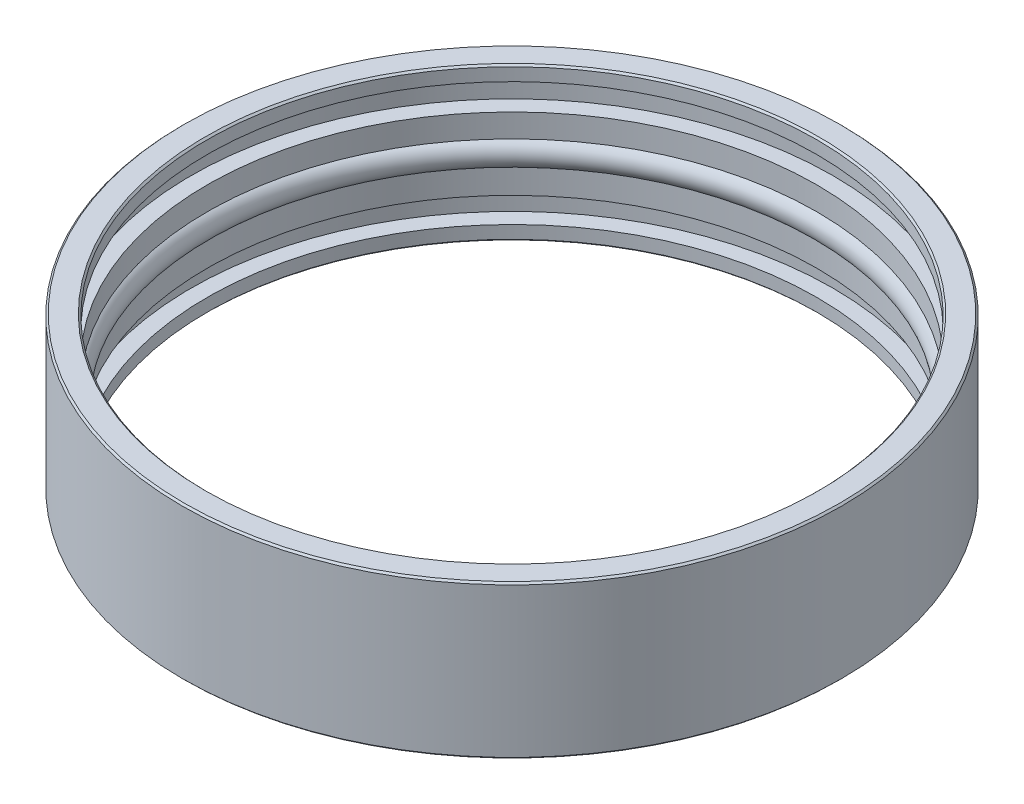
SolidWorks part; units mm, degrees
ref_plane "Plano frontal" through (0, 0, 0) normal (0, 0, 1) x (1, 0, 0)
ref_plane "Plano superior" through (0, 0, 0) normal (0, 1, 0) x (1, 0, 0)
ref_plane "Plano direito" through (0, 0, 0) normal (1, 0, 0) x (0, 0, -1)
sketch "Esboço1" plane through (0, 0, 0) normal (0, 0, 1) x (1, 0, 0)
  line L0 (0, -46.1843) -> (0, 46.7182) construction
  line L1 (52.25, 6.7035) -> (56.5, 6.7035)
  line L2 (56.5, 6.7035) -> (56.5, -19.4965)
  line L3 (56.5, -19.4965) -> (52.25, -19.4965)
  line L4 (52.25, -19.4965) -> (52.25, -16.9965)
  line L5 (52.25, -16.9965) -> (55, -16.9965)
  line L6 (55, -16.9965) -> (55, -12.6707)
  line L7 (55, -12.6707) -> (52.25, -12.6707)
  line L8 (52.25, -12.6707) -> (52.25, -8.4965)
  line L9 (52.25, 6.7035) -> (52.25, 4.2035)
  line L10 (52.25, 4.2035) -> (55, 4.2035)
  line L11 (55, 4.2035) -> (55, -0.2965)
  line L12 (55, -0.2965) -> (52.25, -0.2965)
  line L13 (54.6018, -6.3965) -> (41.8954, -6.3965) construction
  line L14 (52.25, -0.2965) -> (52.25, -4.2965)
  arc A0 (52.25, -8.4965) -> (52.25, -4.2965) centre (53.6065, -6.3965) cw
  dimension "D9" = 2.5
  dimension "D1" = 26.2
  dimension "D2" = 2.5
  dimension "D3" = 2.5
  dimension "D4" = 52.25
  dimension "D5" = 4.5
  dimension "D6" = 13.1
  dimension "D7" = 56.5
  dimension "D8" = 52.25
  dimension "D10" = 11
  dimension "D11" = 11
  dimension "D12" = 2.75
  dimension "D13" = 2.75
revolve "Revolução1" add sketch "Esboço1" angle 360 about L0
chamfer "Chanfro1" distance 0.3 angle 45 4 edges at (0, -19.4965, -52.25) (0, 6.7035, -52.25) (0, -19.4965, -56.5) (0, 6.7035, -56.5)
